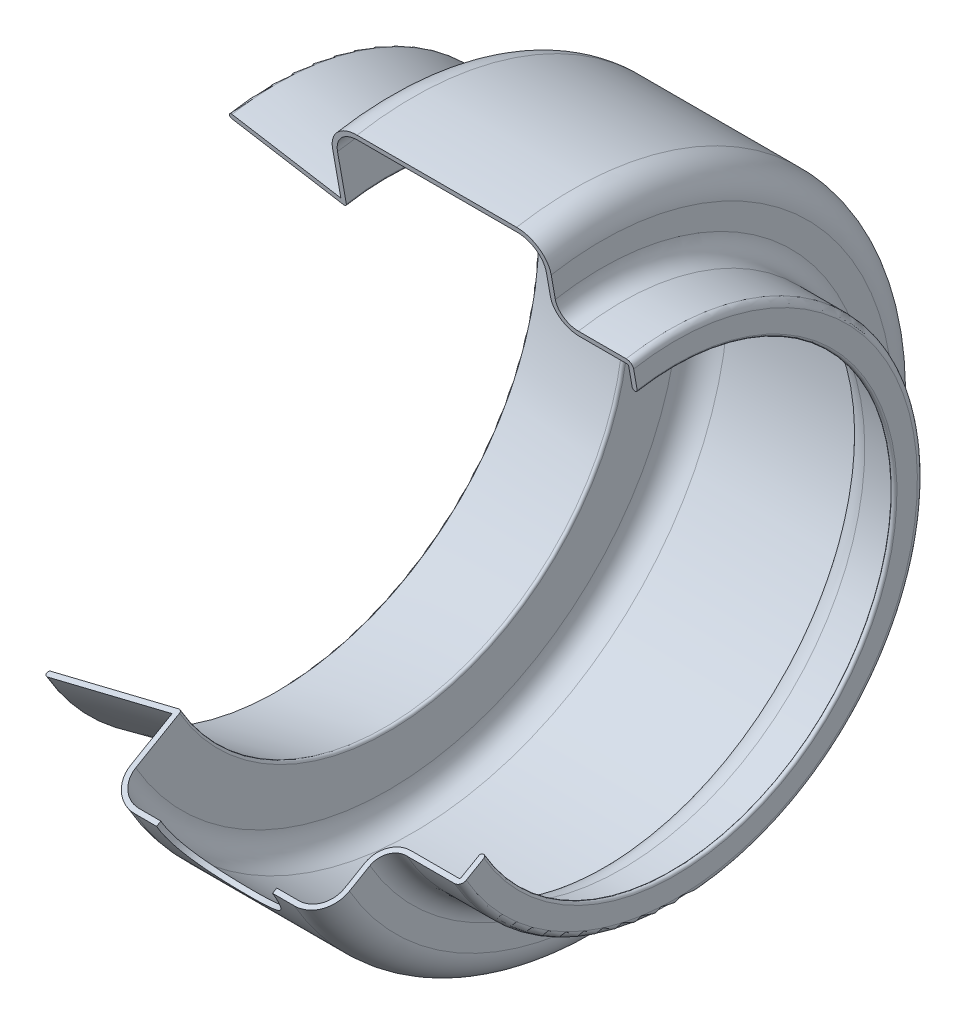
SolidWorks part; units mm, degrees
ref_plane "Front Plane" through (0, 0, 0) normal (0, 0, 1) x (1, 0, 0)
ref_plane "Top Plane" through (0, 0, 0) normal (0, 1, 0) x (1, 0, 0)
ref_plane "Right Plane" through (0, 0, 0) normal (1, 0, 0) x (0, 0, -1)
sketch "Sketch1" plane through (0, 0, 0) normal (0, 0, 1) x (1, 0, 0)
  line L0 (0, 45) -> (0, 49.15)
  line L1 (-1.3, 50.45) -> (-11, 50.45)
  line L2 (-15, 54.45) -> (-15, 59.25)
  line L3 (-21, 65.25) -> (-53.44, 65.25)
  line L4 (-59.44, 59.25) -> (-59.44, 49.57)
  line L5 (-59.44, 49.57) -> (-80.793, 54.1087)
  line L6 (-1, 45) -> (-1, 49.15)
  line L7 (-1.3, 49.45) -> (-11, 49.45)
  line L8 (-16, 54.45) -> (-16, 59.25)
  line L9 (-21, 64.25) -> (-53.44, 64.25)
  line L10 (-58.44, 59.25) -> (-58.44, 48.9526)
  line L11 (-59.044, 48.4635) -> (-81.0009, 53.1306)
  line L12 (0, 45) -> (0, 0) construction
  line L13 (-58.44, 59.25) -> (-58.44, 48.3351) construction
  line L14 (-58.44, 48.3351) -> (-81.0009, 53.1306) construction
  line L15 (0, 0) -> (-65.4005, 0) construction
  arc A0 (0, 49.15) -> (-1.3, 50.45) centre (-1.3, 49.15) ccw
  arc A1 (-11, 50.45) -> (-15, 54.45) centre (-11, 54.45) cw
  arc A2 (-53.44, 65.25) -> (-59.44, 59.25) centre (-53.44, 59.25) ccw
  arc A3 (-15, 59.25) -> (-21, 65.25) centre (-21, 59.25) ccw
  arc A4 (-1, 49.15) -> (-1.3, 49.45) centre (-1.3, 49.15) ccw
  arc A5 (-11, 49.45) -> (-16, 54.45) centre (-11, 54.45) cw
  arc A6 (-16, 59.25) -> (-21, 64.25) centre (-21, 59.25) ccw
  arc A7 (-53.44, 64.25) -> (-58.44, 59.25) centre (-53.44, 59.25) ccw
  arc A8 (-80.793, 54.1087) -> (-81.0009, 53.1306) centre (-80.8969, 53.6196) ccw
  arc A9 (-1, 45) -> (0, 45) centre (-0.5, 45) ccw
  arc A10 (-58.44, 48.9526) -> (-59.044, 48.4635) centre (-58.94, 48.9526) cw
  point P10 (0, 50.45)
  point P13 (-15, 50.45)
  point P16 (-59.44, 65.25)
  point P19 (-15, 65.25)
  dimension "D8" = 1.3
  dimension "D9" = 4
  dimension "D10" = 6
  dimension "D13" = 0.5
  dimension "D1" = 78
  dimension "D2" = 5.45
  dimension "D3" = 15
  dimension "D4" = 14.8
  dimension "D5" = 44.44
  dimension "D6" = 15.68
  dimension "D7" = 21.83
  dimension "D12" = 45
  dimension "D11" = 1
revolve "Revolve1" add sketch "Sketch1" angle 240 about L15
sketch "Sketch2" plane through (0, 0, 0) normal (0, 1, 0) x (1, 0, 0)
  line L0 (-21, -11.3305) -> (-53.44, -11.3305) construction
  circle A0 centre (-37.22, -11.3305) radius 11.74
  dimension "D1" = 23.48
ref_plane "Plane1" through (0, -32.625, 56.5082) normal (0, -0.5, 0.866) x (1, 0, 0)
sketch "Sketch3" plane through (0, -32.625, 56.5082) normal (0, -0.5, 0.866) x (1, 0, 0)
  circle A0 centre (-37.22, -0.2047) radius 11.79
  ellipse E0 centre (-37.22, 5.6653) end of major axis (-25.48, 5.6653) minor radius 5.87 construction
  dimension "D1" = 23.58
extrude "Cut-Extrude1" cut sketch "Sketch3" against normal blind 10
